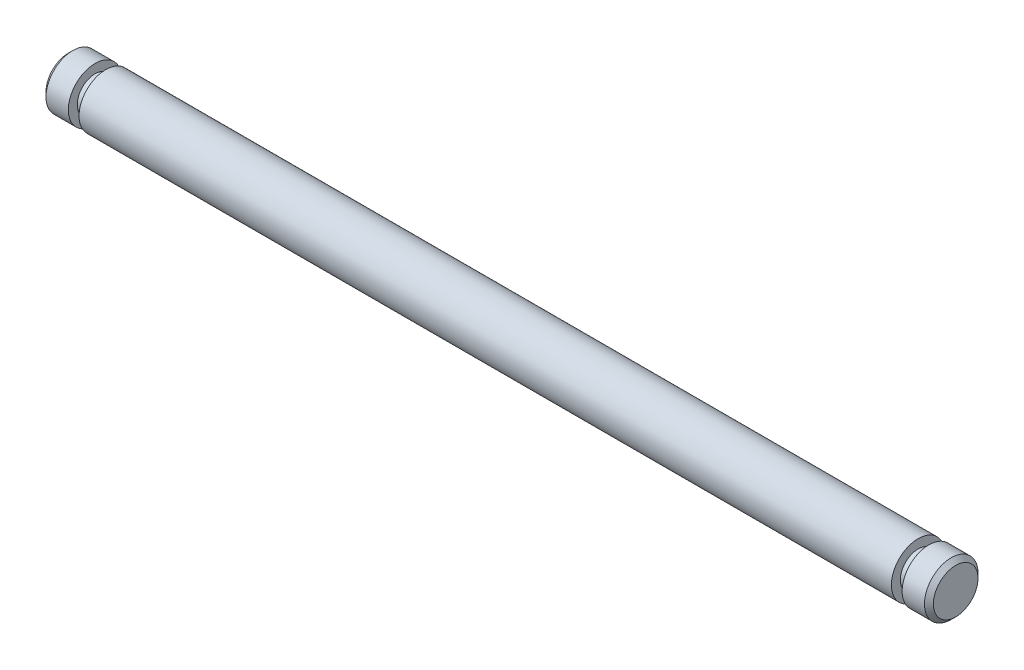
SolidWorks part; units mm, degrees
material "Chrome Stainless Steel"
ref_plane "Front Plane" through (0, 0, 0) normal (0, 0, 1) x (1, 0, 0)
ref_plane "Top Plane" through (0, 0, 0) normal (0, 1, 0) x (1, 0, 0)
ref_plane "Right Plane" through (0, 0, 0) normal (1, 0, 0) x (0, 0, -1)
sketch "Sketch2" plane through (0, 0, 0) normal (0, 0, 1) x (1, 0, 0)
  line L0 (22.75, 1.5) -> (-22.75, 1.5)
  line L1 (-22.75, 1.5) -> (-22.75, 1)
  line L2 (-22.75, 1) -> (-23.35, 1)
  line L3 (-23.35, 1) -> (-23.35, 1.5)
  line L4 (-23.35, 1.5) -> (-24.85, 1.5)
  line L5 (-24.85, 1.5) -> (-24.85, 0)
  line L6 (-24.85, 0) -> (24.85, 0)
  line L7 (0, -55) -> (0, 55) construction
  line L8 (24.85, 1.5) -> (24.85, 0)
  line L9 (23.35, 1.5) -> (24.85, 1.5)
  line L10 (23.35, 1) -> (23.35, 1.5)
  line L11 (22.75, 1) -> (23.35, 1)
  line L12 (22.75, 1.5) -> (22.75, 1)
  line L13 (-61.7565, 0) -> (-50061.7565, 0) construction
  point P12 (0, 0)
  point P17 (0, 1.5)
  dimension "D1" = 0.6
  dimension "D2" = 3
  dimension "D3" = 2
  dimension "D4" = 2.1
  dimension "D5" = 49.7
revolve "Revolve1" add sketch "Sketch2" angle 360 about L13
chamfer "Chamfer1" distance 0.25 angle 45 2 edges at (-24.85, 0, -1.5) (24.85, 0, -1.5)
